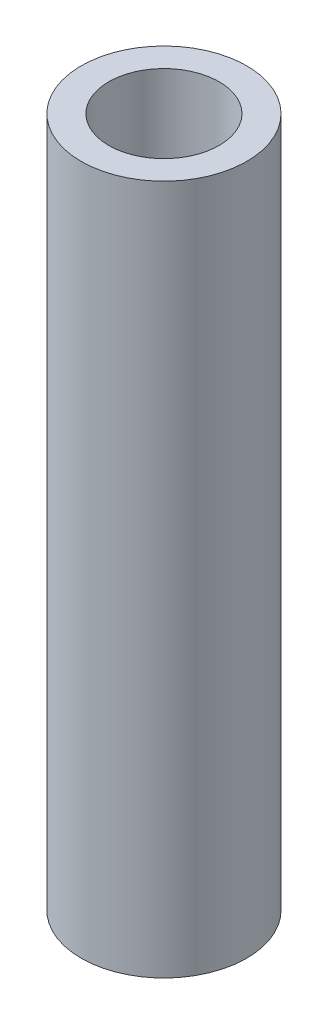
SolidWorks part; units mm, degrees
ref_plane "Front" through (0, 0, 0) normal (0, 0, 1) x (1, 0, 0)
ref_plane "Top" through (0, 0, 0) normal (0, 1, 0) x (1, 0, 0)
ref_plane "Right" through (0, 0, 0) normal (1, 0, 0) x (0, 0, -1)
sketch "Sketch1" plane through (0, 0, 0) normal (0, 1, 0) x (1, 0, 0)
  circle A0 centre (0, 0) radius 3
  circle A1 centre (0, 0) radius 2
  dimension "D1" = 6
  dimension "D2" = 4
extrude "Boss-Extrude1" add sketch "Sketch1" along normal blind 25
